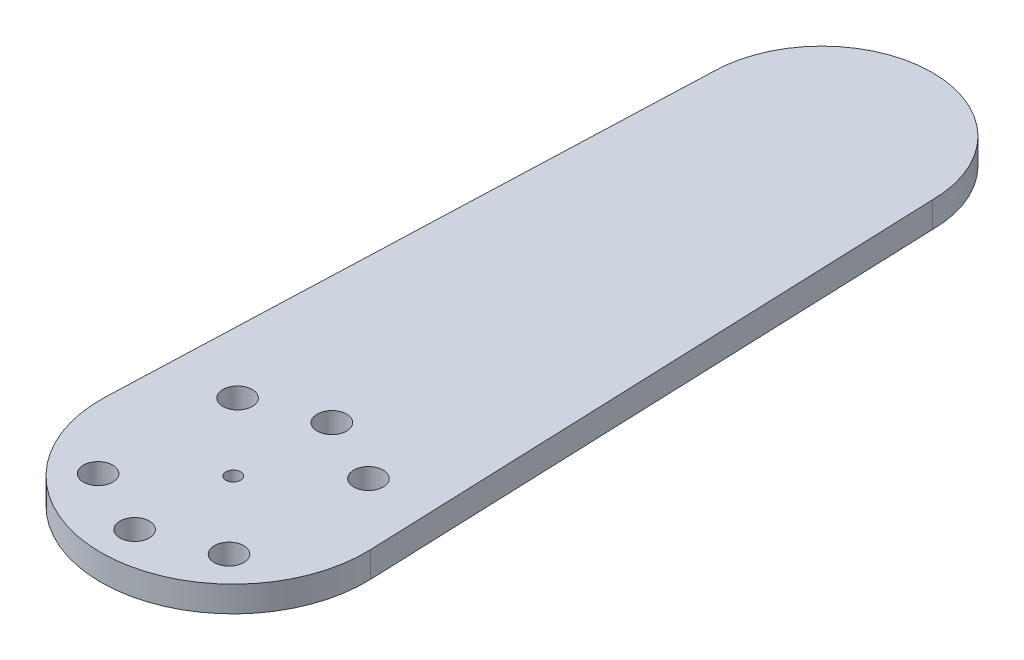
SolidWorks part; units mm, degrees
ref_plane "Спереди" through (0, 0, 0) normal (0, 0, 1) x (1, 0, 0)
ref_plane "Сверху" through (0, 0, 0) normal (0, 1, 0) x (1, 0, 0)
ref_plane "Справа" through (0, 0, 0) normal (1, 0, 0) x (0, 0, -1)
sketch "Эскиз1" plane through (0, 0, 0) normal (0, 1, 0) x (1, 0, 0)
  line L0 (-15, 80) -> (-17.9872, 0.6774)
  line L1 (15, 80) -> (17.9872, 0.6774)
  arc A0 (-17.9872, 0.6774) -> (17.9872, 0.6774) centre (0, 0) ccw
  circle A2 centre (0, 0) radius 1
  arc A3 (15, 80) -> (-15, 80) centre (0, 80) ccw
  dimension "D1" = 80
extrude "Вытянуть1" add sketch "Эскиз1" along normal blind 3.5
sketch "Эскиз2" plane through (0, 0, 0) normal (0, -1, 0) x (1, 0, 0)
  circle A0 centre (-0.409, 12.9936) radius 2
  circle A1 centre (-9.477, 8.8986) radius 2
  circle A2 centre (8.8986, 9.477) radius 2
  circle A3 centre (9.477, -8.8986) radius 2
  circle A4 centre (0.409, -12.9936) radius 2
  circle A5 centre (-8.8986, -9.477) radius 2
extrude "Вырез-Вытянуть1" cut sketch "Эскиз2" against normal through all
